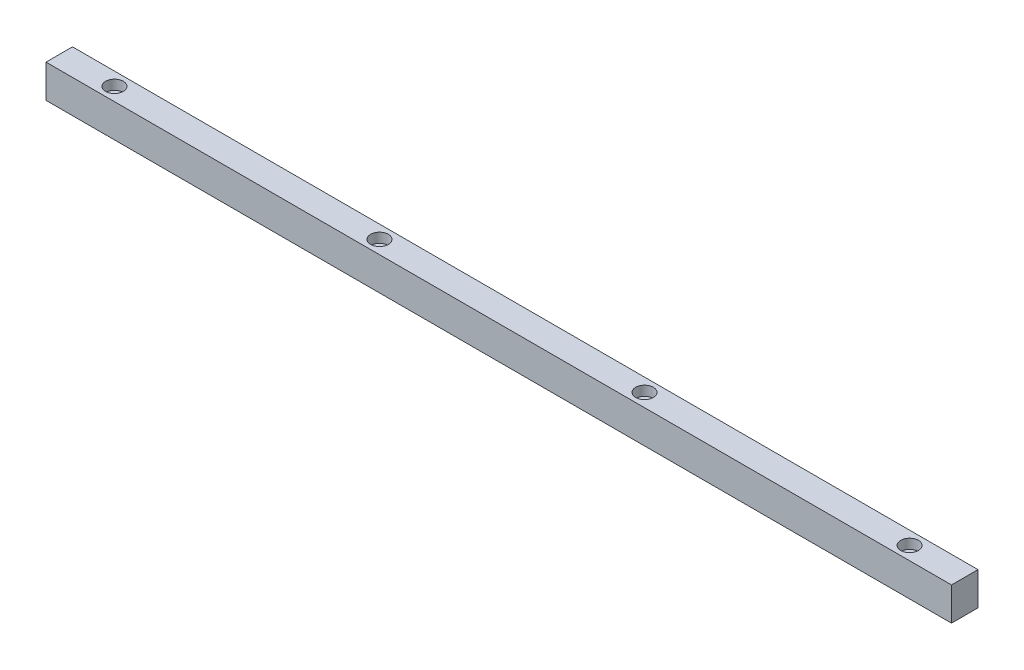
SolidWorks part; units mm, degrees
material "防静电研磨黑纤"
ref_plane "前视基准面" through (0, 0, 0) normal (0, 0, 1) x (1, 0, 0)
ref_plane "上视基准面" through (0, 0, 0) normal (0, 1, 0) x (1, 0, 0)
ref_plane "右视基准面" through (0, 0, 0) normal (1, 0, 0) x (0, 0, -1)
sketch "草图1" plane through (0, 0, 0) normal (0, 1, 0) x (1, 0, 0)
  line L1 (-205, 6) -> (205, 6)
  line L2 (-205, 6) -> (-205, -6)
  line L3 (-205, -6) -> (205, -6)
  line L4 (205, 6) -> (205, -6)
  line L5 (-205, 6) -> (205, -6) construction
  line L6 (-205, -6) -> (205, 6) construction
  point P0 (0, 0)
  dimension "D1" = 12
  dimension "D2" = 410
extrude "凸台-拉伸1" add sketch "草图1" along normal blind 15
hole_wizard "M4 六角凹头螺钉的柱形沉头孔1" positions "草图2" profile "草图3" counterbore size "M4" standard "ISO" end condition through all
sketch "草图2" plane through (0, 15, 0) normal (0, 1, 0) x (1, 0, 0)
  line L0 (-205, 0) -> (205, 0) construction
  line L1 (-205, 6) -> (-205, -6) construction
  line L2 (205, -6) -> (205, 6) construction
  line L3 (0, 6) -> (0, 68.7357) construction
  line L4 (205, 6) -> (-205, 6) construction
  point P9 (-60, 0)
  point P11 (-180, 0)
  point P21 (180, 0)
  point P22 (60, 0)
  dimension "D1" = 60
  dimension "D2" = 120
sketch "草图3" plane through (60, 15, 0) normal (1, 0, 0) x (0, 0, 1)
  line L0 (0, 0) -> (0, 15)
  line L1 (0, 15) -> (2.25, 15)
  line L3 (2.25, 15) -> (2.25, 4.4)
  line L4 (2.25, 4.4) -> (4, 4.4)
  line L5 (4, 4.4) -> (4, 0)
  line L7 (4, 0) -> (0, 0)
  line L11 (0, -6.35) -> (0, 107.95) construction
  dimension "通孔孔直径" = 4.5
  dimension "通孔孔深度" = 15
  dimension "柱形沉头孔直径" = 8
  dimension "柱形沉头孔深度" = 4.4
